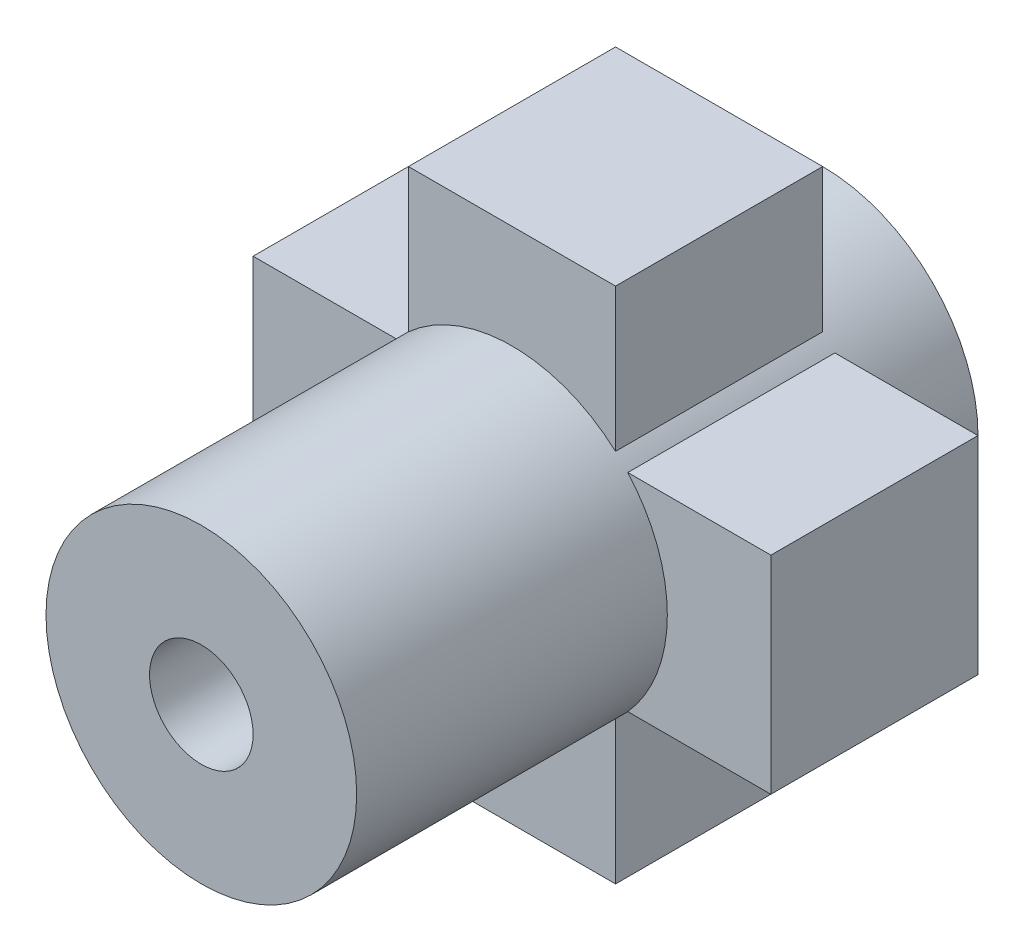
SolidWorks part; units mm, degrees
ref_plane "Front Plane" through (0, 0, 0) normal (0, 0, 1) x (1, 0, 0)
ref_plane "Top Plane" through (0, 0, 0) normal (0, 1, 0) x (1, 0, 0)
ref_plane "Right Plane" through (0, 0, 0) normal (1, 0, 0) x (0, 0, -1)
sketch "Sketch1" plane through (0, 0, 0) normal (0, 0, 1) x (1, 0, 0)
  line L0 (-5.5902, -5) -> (-12.5, -5)
  line L2 (-5, -5.5902) -> (-5, -12.5)
  line L3 (-5, -12.5) -> (5, -12.5)
  line L4 (5, -5.5902) -> (5, -12.5)
  line L5 (2.7854, -6.9636) -> (5, -12.5) construction
  line L6 (-5, -12.5) -> (-2.7854, -6.9636) construction
  line L7 (-12.5, 5) -> (-12.5, -5)
  line L8 (-5.5902, 5) -> (-12.5, 5)
  line L9 (-5, 5.5902) -> (-5, 12.5)
  line L10 (5, 12.5) -> (-5, 12.5)
  line L11 (5, 5.5902) -> (5, 12.5)
  line L12 (5.5902, 5) -> (12.5, 5)
  line L13 (12.5, -5) -> (12.5, 5)
  line L14 (5.5902, -5) -> (12.5, -5)
  circle A0 centre (0, 0) radius 2.5
  circle A1 centre (0, 0) radius 7.5
  arc A2 (-5, -5.5902) -> (5, -5.5902) centre (0, 0) ccw
  arc A3 (-5.5902, 5) -> (-5.5902, -5) centre (0, 0) ccw
  arc A4 (5, 5.5902) -> (-5, 5.5902) centre (0, 0) ccw
  arc A5 (5.5902, -5) -> (5.5902, 5) centre (0, 0) ccw
  point P26 (0, 0)
  dimension "D1" = 5
  dimension "D2" = 15
  dimension "D3" = 10
  dimension "D4" = 4
extrude "Boss-Extrude1" add sketch "Sketch1" along normal blind 10 contours A1 L8 L7 L0 | A1 L2 L3 L4 | A1 L11 L10 L9 | A1 L14 L13 L12 | A1 A0
sketch "Sketch2" plane through (0, 0, 10) normal (0, 0, 1) x (1, 0, 0)
  circle A0 centre (0, 0) radius 2.5
  circle A1 centre (0, 0) radius 7.5
  dimension "D1" = 5
  dimension "D2" = 15
extrude "Boss-Extrude2" add sketch "Sketch2" along normal blind 15 and the other way blind 15
